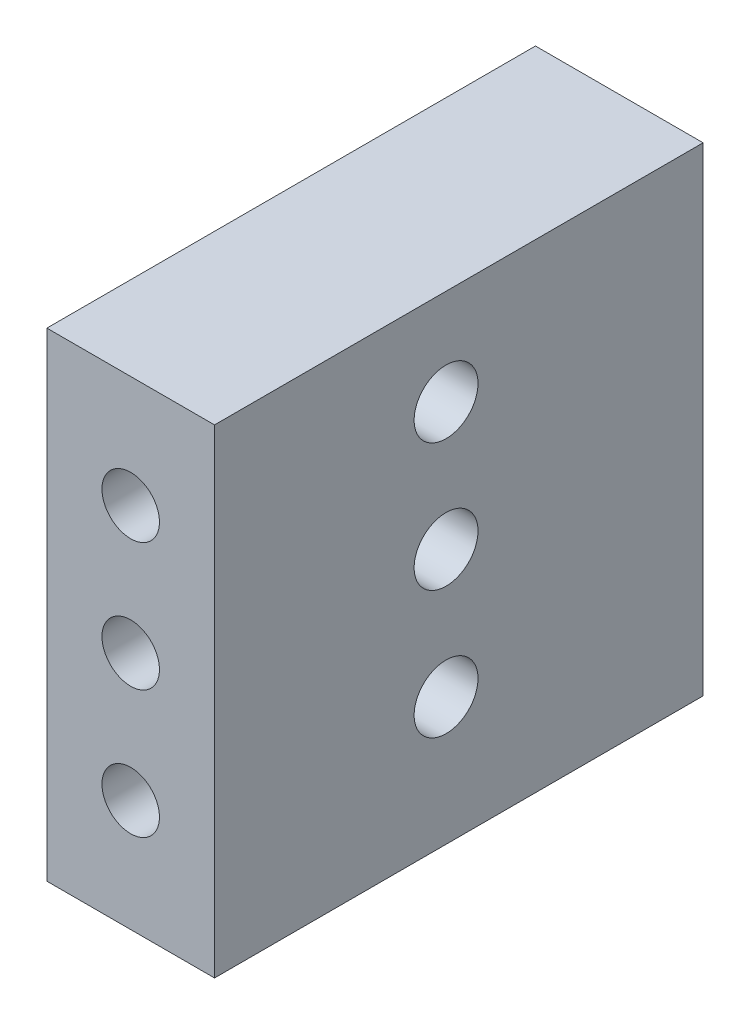
SolidWorks part; units mm, degrees
material "ABS"
ref_plane "前基準面" through (0, 0, 0) normal (0, 0, 1) x (1, 0, 0)
ref_plane "上基準面" through (0, 0, 0) normal (0, 1, 0) x (1, 0, 0)
ref_plane "右基準面" through (0, 0, 0) normal (1, 0, 0) x (0, 0, -1)
sketch "草圖1" plane through (0, 0, 0) normal (0, 1, 0) x (1, 0, 0)
  line L11 (0, 0) -> (10.5, 0)
  line L12 (0, 0) -> (0, 38.1)
  line L13 (0, 38.1) -> (10.5, 38.1)
  line L14 (10.5, 0) -> (10.5, 38.1)
  dimension "D1" = 10.5
  dimension "D2" = 38.1
extrude "填料-伸長1" add sketch "草圖1" along normal blind 30
sketch "草圖2" plane through (10.5, 0, 0) normal (1, 0, 0) x (0, 0, -1)
  line L0 (0, 0) -> (38.1, 0) construction
  line L1 (0, 30) -> (0, 0) construction
  circle A0 centre (22, 24) radius 2
  circle A1 centre (22, 16) radius 2
  circle A2 centre (22, 8) radius 2
  dimension "D1" = 4
  dimension "D2" = 8
  dimension "D3" = 8
  dimension "D4" = 8
  dimension "D5" = 22
extrude "除料-伸長1" cut sketch "草圖2" against normal blind 11
sketch "草圖3" plane through (0, 0, 0) normal (0, 0, 1) x (1, 0, 0)
  line L0 (0, 30) -> (10.5, 30) construction
  line L2 (0, 30) -> (0, 0) construction
  circle A0 centre (5.25, 23) radius 1.8
  circle A1 centre (5.25, 15) radius 1.8
  circle A2 centre (5.25, 7) radius 1.8
  dimension "D3" = 3.6
  dimension "D1" = 8
  dimension "D2" = 8
  dimension "D4" = 7
  dimension "D5" = 5.25
extrude "除料-伸長2" cut sketch "草圖3" against normal blind 17
sketch "草圖4" plane through (0, 0, -38.1) normal (0, 0, -1) x (-1, 0, 0)
  line L0 (-10.5, 0) -> (0, 0) construction
  line L1 (0, 30) -> (0, 0) construction
  circle A0 centre (-6.25, 26) radius 1.8
  circle A1 centre (-6.25, 18) radius 1.8
  circle A2 centre (-6.25, 10) radius 1.8
  dimension "D1" = 3.6
  dimension "D2" = 8
  dimension "D3" = 8
  dimension "D4" = 10
  dimension "D5" = 6.25
extrude "除料-伸長3" cut sketch "草圖4" against normal blind 9
sketch "草圖5" plane through (0, 30, 0) normal (0, 1, 0) x (1, 0, 0)
  line L0 (10.5, 0) -> (10.5, 38.1) construction
  line L1 (0, 0) -> (10.5, 0)
  line L2 (0, 0) -> (0, 7.5)
  line L3 (0, 7.5) -> (10.5, 7.5)
  line L4 (10.5, 0) -> (10.5, 7.5)
  dimension "D1" = 7.5
extrude "除料-伸長4" cut sketch "草圖5" against normal up to vertex (30 mm away)
